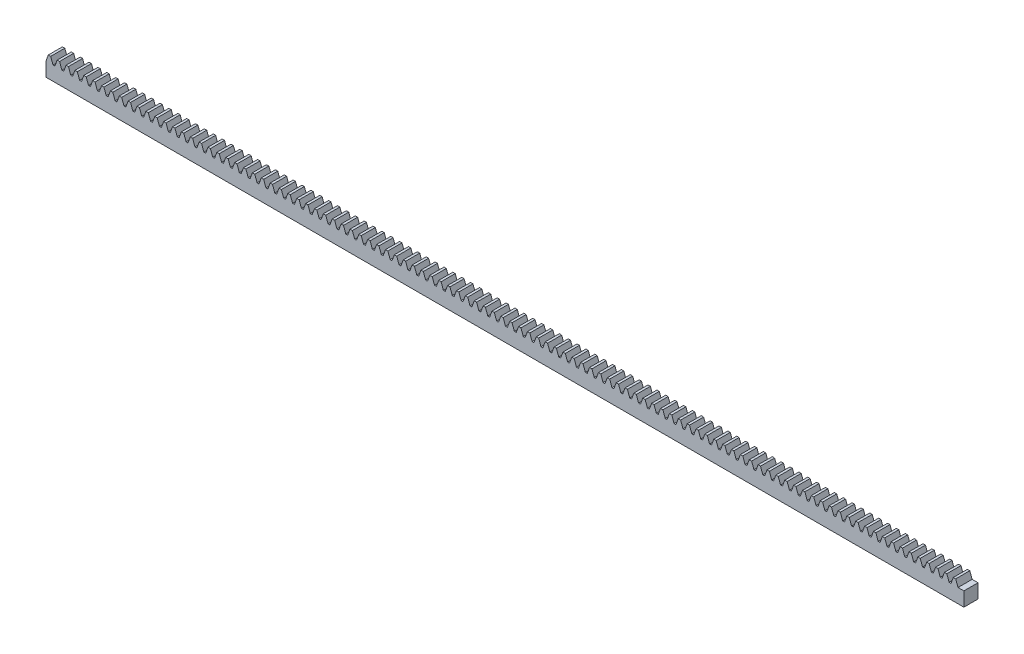
SolidWorks part; units mm, degrees
ref_plane "前视基准面" through (0, 0, 0) normal (0, 0, 1) x (1, 0, 0)
ref_plane "上视基准面" through (0, 0, 0) normal (0, 1, 0) x (1, 0, 0)
ref_plane "右视基准面" through (0, 0, 0) normal (1, 0, 0) x (0, 0, -1)
sketch "草图1" plane through (0, 0, 0) normal (0, 0, 1) x (1, 0, 0)
  line L1 (0, 0) -> (650, 0)
  line L2 (0, 0) -> (0, -10)
  line L3 (0, -10) -> (650, -10)
  line L4 (650, 0) -> (650, -10)
  dimension "D1" = 10
  dimension "L" = 650
extrude "拉伸1" add sketch "草图1" along normal blind 10
sketch "草图2" plane through (0, 0, 10) normal (0, 0, 1) x (1, 0, 0)
  line L0 (0, 0) -> (1.6379, 4.5)
  line L1 (1.6379, 4.5) -> (3.3236, 4.5)
  line L2 (3.3236, 4.5) -> (4.9614, 0)
  line L3 (650, 0) -> (0, 0) construction
  line L4 (0, 0) -> (4.9614, 0)
  line L5 (0.9099, 2.5) -> (4.0515, 2.5) construction
  dimension "D2" = 70
  dimension "alpha" = 110
  dimension "ha" = 2
  dimension "hf" = 2.5
  dimension "S" = 3.1416
extrude "拉伸2" add sketch "草图2" against normal up to surface (10 mm away) up to face at (325, -5, 0)
pattern_linear "阵列(线性)1" count 103 spacing 6.2832 along (1, 0, 0) of "拉伸2"
equation "\"d\"=\"S@草图2\" * 2"
equation "\"z\"= int(  \"L@草图1\" / (  \"S@草图2\" * 2 ) + 0.5 )"
